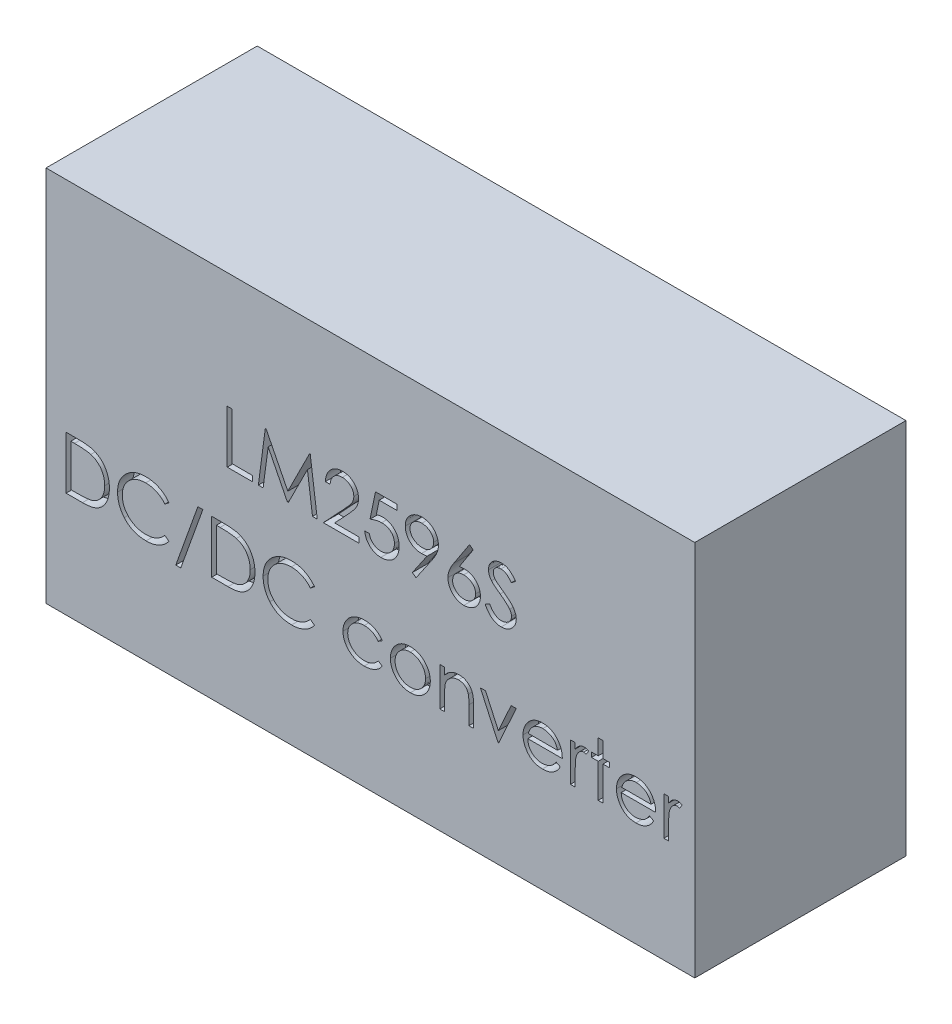
SolidWorks part; units mm, degrees
ref_plane "정면" through (0, 0, 0) normal (0, 0, 1) x (1, 0, 0)
ref_plane "윗면" through (0, 0, 0) normal (0, 1, 0) x (1, 0, 0)
ref_plane "우측면" through (0, 0, 0) normal (1, 0, 0) x (0, 0, -1)
sketch "스케치2" plane through (0, 0, 0) normal (0, 0, 1) x (1, 0, 0)
  line L1 (-21.5, 12.5) -> (21.5, 12.5)
  line L2 (-21.5, 12.5) -> (-21.5, -12.5)
  line L3 (-21.5, -12.5) -> (21.5, -12.5)
  line L4 (21.5, 12.5) -> (21.5, -12.5)
  line L5 (-21.5, 12.5) -> (21.5, -12.5) construction
  line L6 (-21.5, -12.5) -> (21.5, 12.5) construction
  point P0 (0, 0)
  dimension "D1" = 25
  dimension "4.5" = 43
extrude "보스-돌출1" add sketch "스케치2" along normal blind 14
sketch "스케치3" plane through (0, 0, 14) normal (0, 0, 1) x (1, 0, 0)
  line L0 (-21.5, 1.3292) -> (21.5, 1.3292) construction
  line L1 (-21.5, 12.5) -> (-21.5, -12.5) construction
  line L2 (21.5, -12.5) -> (21.5, 12.5) construction
  text T0 "LM2596S\r\nDC/DC converter"
extrude "컷-돌출1" cut sketch "스케치3" against normal blind 1
